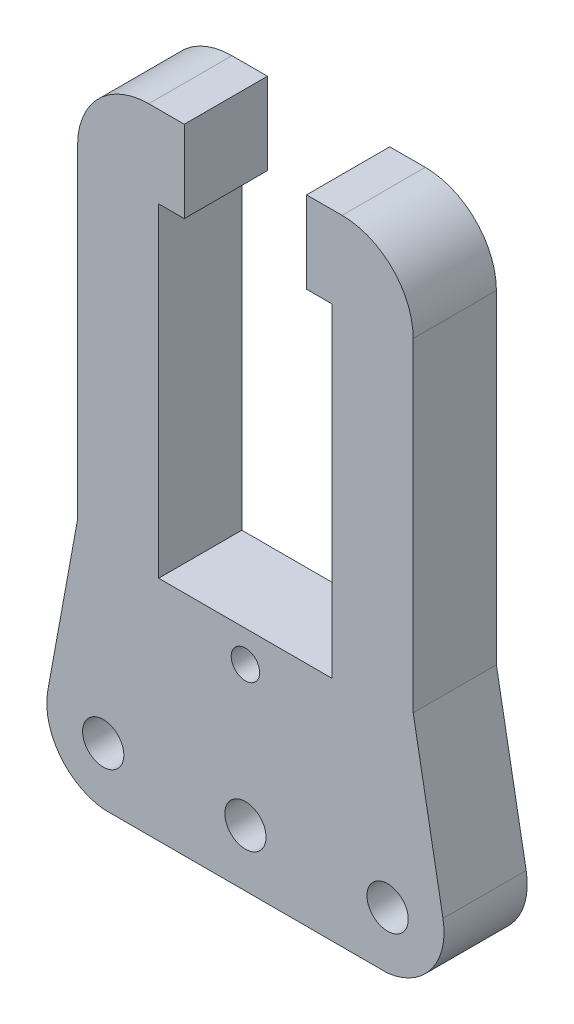
SolidWorks part; units mm, degrees
material "Acrylic (Medium-high impact)"
ref_plane "Front Plane" through (0, 0, 0) normal (0, 0, 1) x (1, 0, 0)
ref_plane "Top Plane" through (0, 0, 0) normal (0, 1, 0) x (1, 0, 0)
ref_plane "Right Plane" through (0, 0, 0) normal (1, 0, 0) x (0, 0, -1)
sketch "Model" plane through (0, 0, 0) normal (0, 0, 1) x (1, 0, 0)
  line L0 (519.9822, -457.799) -> (519.9822, 49542.201) construction
  line L1 (508.1822, 554.9348) -> (506.0873, 543.4616)
  line L2 (519.9822, 542.1848) -> (509.9822, 542.1848) construction
  line L3 (513.8822, 554.1848) -> (526.0822, 554.1848)
  line L4 (509.9822, 538.1848) -> (529.9822, 538.1848)
  line L5 (508.1822, 577.7348) -> (508.1822, 554.9348)
  line L6 (515.6822, 582.7348) -> (513.1822, 582.7348)
  line L7 (515.6822, 576.9848) -> (515.6822, 582.7348)
  line L8 (513.8822, 576.9848) -> (515.6822, 576.9848)
  line L9 (513.8822, 554.1848) -> (513.8822, 576.9848)
  line L10 (519.9822, 542.1848) -> (529.9822, 542.1848) construction
  line L80 (526.0822, 554.1848) -> (526.0822, 576.9848)
  line L81 (526.0822, 576.9848) -> (524.2822, 576.9848)
  line L82 (524.2822, 576.9848) -> (524.2822, 582.7348)
  line L83 (524.2822, 582.7348) -> (526.7822, 582.7348)
  line L84 (531.7822, 577.7348) -> (531.7822, 554.9348)
  line L85 (531.7822, 554.9348) -> (533.8772, 543.4616)
  circle A0 centre (509.9822, 542.1848) radius 1.45
  arc A1 (526.7822, 582.7348) -> (531.7822, 577.7348) centre (526.7822, 577.7348) cw
  arc A2 (506.0873, 543.4616) -> (509.9822, 538.1848) centre (510.5141, 542.6533) ccw
  arc A3 (533.8772, 543.4616) -> (529.9822, 538.1848) centre (529.4504, 542.6533) cw
  arc A4 (513.1822, 582.7348) -> (508.1822, 577.7348) centre (513.1822, 577.7348) ccw
  circle A5 centre (519.9822, 542.1848) radius 1.45
  circle A6 centre (529.9822, 542.1848) radius 1.45
  circle A7 centre (519.9822, 551.9848) radius 1
  point P2 (519.9822, 554.1848)
  point P5 (519.9822, 538.1848)
  point P6 (519.9822, 554.1848)
  point P13 (519.9822, 538.1848)
  dimension "D4" = 2.9
  dimension "D9" = 4.5
  dimension "D11" = 5
  dimension "D14" = 2
  dimension "D1" = 12.2
  dimension "D2" = 22.8
  dimension "D3" = 10
  dimension "D5" = 4
  dimension "D6" = 12
  dimension "D7" = 5.75
  dimension "D8" = 1.8
  dimension "D10" = 11.4732
  dimension "D12" = 20
  dimension "D13" = 2.5
  dimension "D15" = 2.2
extrude "Boss-Extrude1" add sketch "Model" along normal blind 5.85
